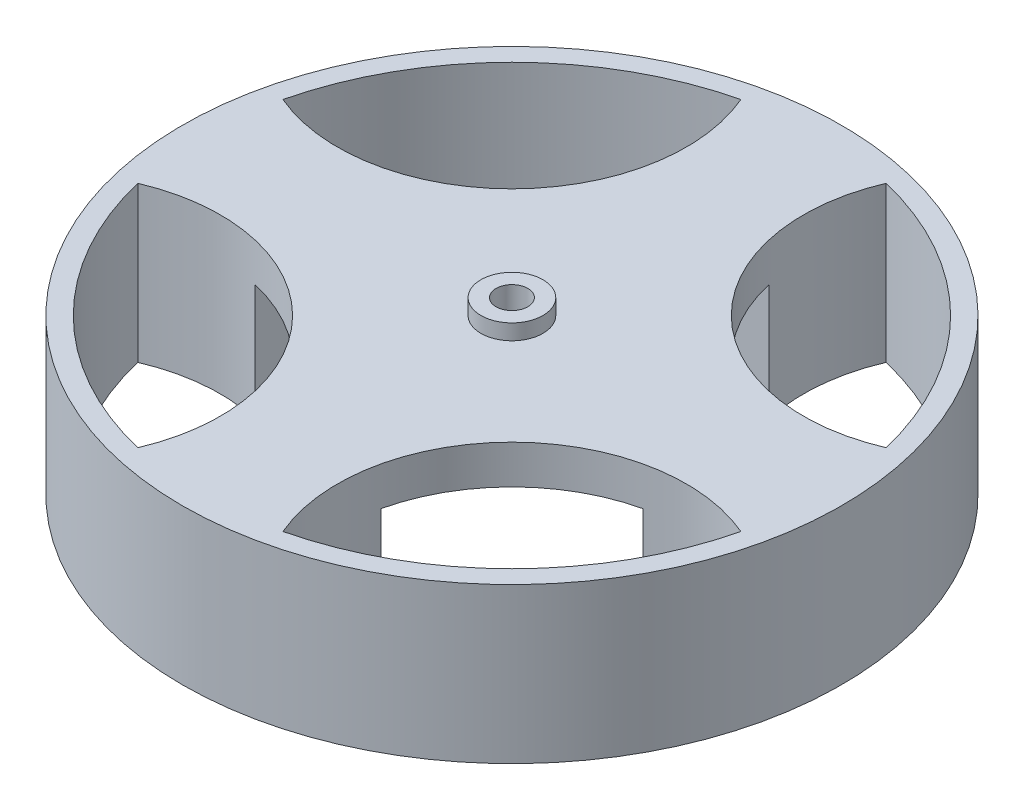
SolidWorks part; units mm, degrees
material "PLA"
ref_plane "Front Plane" through (0, 0, 0) normal (0, 0, 1) x (1, 0, 0)
ref_plane "Top Plane" through (0, 0, 0) normal (0, 1, 0) x (1, 0, 0)
ref_plane "Right Plane" through (0, 0, 0) normal (1, 0, 0) x (0, 0, -1)
sketch "Sketch1" plane through (0, 0, 0) normal (0, 1, 0) x (1, 0, 0)
  circle A0 centre (0, 0) radius 42.5
  circle A1 centre (0, 0) radius 40
  dimension "D1" = 85
  dimension "D2" = 80
extrude "Boss-Extrude1" add sketch "Sketch1" along normal mid plane 20
sketch "Sketch2" plane through (0, 10, 0) normal (0, 1, 0) x (1, 0, 0)
  line L0 (-42.5, 0) -> (42.5, 0) construction
  line L1 (0, 42.5) -> (0, -42.5) construction
  line L2 (-34.2667, -34.2667) -> (34.2667, 34.2667) construction
  line L3 (37.762, -37.762) -> (-37.762, 37.762) construction
  circle A0 centre (0, 0) radius 42.5 construction
  arc A1 (-38.8894, 9.3602) -> (-9.3602, 38.8894) centre (-30.052, 30.052) ccw
  arc A2 (9.3602, 38.8894) -> (38.8894, 9.3602) centre (30.052, 30.052) ccw
  arc A3 (38.8894, -9.3602) -> (9.3602, -38.8894) centre (30.052, -30.052) ccw
  arc A4 (-9.3602, -38.8894) -> (-38.8894, -9.3602) centre (-30.052, -30.052) ccw
  circle A5 centre (0, 0) radius 40 construction
  arc A6 (9.3602, 38.8894) -> (-9.3602, 38.8894) centre (0, 0) ccw
  arc A7 (-38.8894, 9.3602) -> (-38.8894, -9.3602) centre (0, 0) ccw
  arc A8 (-9.3602, -38.8894) -> (9.3602, -38.8894) centre (0, 0) ccw
  arc A9 (38.8894, -9.3602) -> (38.8894, 9.3602) centre (0, 0) ccw
  point P10 (0, 0)
  point P14 (0, 0)
  dimension "D3" = 45
  dimension "D1" = 45
  dimension "D2" = 45
extrude "Boss-Extrude2" add sketch "Sketch2" against normal blind 5
sketch "Sketch3" plane through (0, 10, 0) normal (0, 1, 0) x (1, 0, 0)
  circle A0 centre (0, 0) radius 4
  circle A1 centre (0, 0) radius 2.05
  dimension "D1" = 8
  dimension "D2" = 4.1
extrude "Boss-Extrude3" add sketch "Sketch3" along normal blind 2
sketch "Sketch4" plane through (0, 10, 0) normal (0, 1, 0) x (1, 0, 0)
  circle A0 centre (0, 0) radius 2.05
  dimension "D1" = 4.1
extrude "Cut-Extrude1" cut sketch "Sketch4" against normal through all
sketch "Sketch5" plane through (0, 5, 0) normal (0, -1, 0) x (1, 0, 0)
  line L0 (-40, 0) -> (-1.6862, 0) construction
  line L2 (-25, -8.1266) -> (-25, 8.1266)
  line L3 (-8.1266, 25) -> (8.1266, 25)
  line L4 (25, 8.1266) -> (25, -8.1266)
  line L5 (8.1266, -25) -> (-8.1266, -25)
  circle A0 centre (0, 0) radius 40 construction
  arc A4 (9.3602, 38.8894) -> (-9.3602, 38.8894) centre (0, 0) ccw
  arc A5 (-8.1266, 25) -> (-9.3602, 38.8894) centre (-30.052, 30.052) ccw
  arc A6 (9.3602, 38.8894) -> (8.1266, 25) centre (30.052, 30.052) ccw
  arc A7 (38.8894, -9.3602) -> (38.8894, 9.3602) centre (0, 0) ccw
  arc A8 (25, 8.1266) -> (38.8894, 9.3602) centre (30.052, 30.052) ccw
  arc A9 (38.8894, -9.3602) -> (25, -8.1266) centre (30.052, -30.052) ccw
  arc A10 (-9.3602, -38.8894) -> (9.3602, -38.8894) centre (0, 0) ccw
  arc A11 (8.1266, -25) -> (9.3602, -38.8894) centre (30.052, -30.052) ccw
  arc A12 (-38.8894, 9.3602) -> (-38.8894, -9.3602) centre (0, 0) ccw
  arc A13 (-9.3602, -38.8894) -> (-38.8894, -9.3602) centre (-30.052, -30.052) ccw
  arc A14 (-9.3602, -38.8894) -> (9.3602, -38.8894) centre (0, 0) ccw
  arc A15 (38.8894, -9.3602) -> (9.3602, -38.8894) centre (30.052, -30.052) ccw
  arc A16 (38.8894, -9.3602) -> (38.8894, 9.3602) centre (0, 0) ccw
  arc A17 (9.3602, 38.8894) -> (38.8894, 9.3602) centre (30.052, 30.052) ccw
  arc A18 (9.3602, 38.8894) -> (-9.3602, 38.8894) centre (0, 0) ccw
  arc A19 (-38.8894, 9.3602) -> (-9.3602, 38.8894) centre (-30.052, 30.052) ccw
  arc A20 (-38.8894, 9.3602) -> (-38.8894, -9.3602) centre (0, 0) ccw
  arc A21 (-25, -8.1266) -> (-38.8894, -9.3602) centre (-30.052, -30.052) ccw
  arc A27 (-38.8894, 9.3602) -> (-25, 8.1266) centre (-30.052, 30.052) ccw
  arc A28 (-9.3602, -38.8894) -> (-8.1266, -25) centre (-30.052, -30.052) ccw
  point P44 (0, 0)
  dimension "D1" = 0
  dimension "D2" = 25
  dimension "D3" = 4
extrude "Boss-Extrude4" add sketch "Sketch5" along normal blind 15
